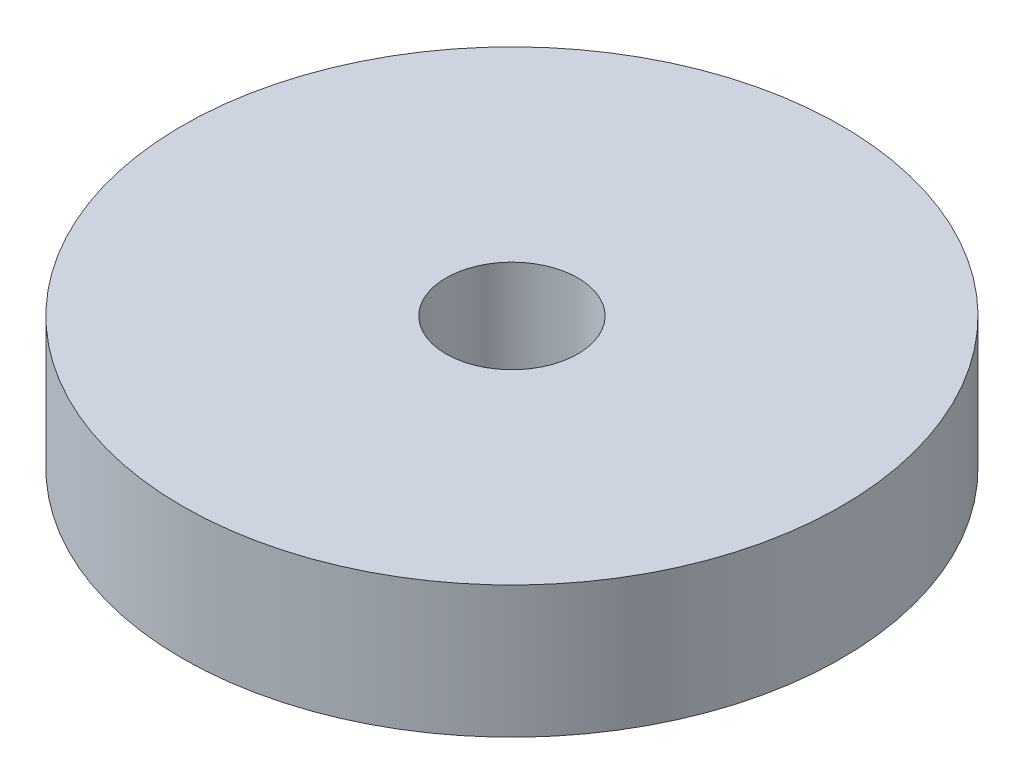
SolidWorks part; units mm, degrees
ref_plane "Front Plane" through (0, 0, 0) normal (0, 0, 1) x (1, 0, 0)
ref_plane "Top Plane" through (0, 0, 0) normal (0, 1, 0) x (1, 0, 0)
ref_plane "Right Plane" through (0, 0, 0) normal (1, 0, 0) x (0, 0, -1)
sketch "Sketch1" plane through (0, 0, 0) normal (0, 1, 0) x (1, 0, 0)
  circle A0 centre (0, 0) radius 25
  dimension "D1" = 50
extrude "Boss-Extrude1" add sketch "Sketch1" along normal blind 10
sketch "Sketch2" plane through (0, 10, 0) normal (0, 1, 0) x (1, 0, 0)
  circle A0 centre (0, 0) radius 5
  circle A1 centre (0, 0) radius 25 construction
  dimension "D1" = 20
extrude "Cut-Extrude1" cut sketch "Sketch2" against normal blind 10
